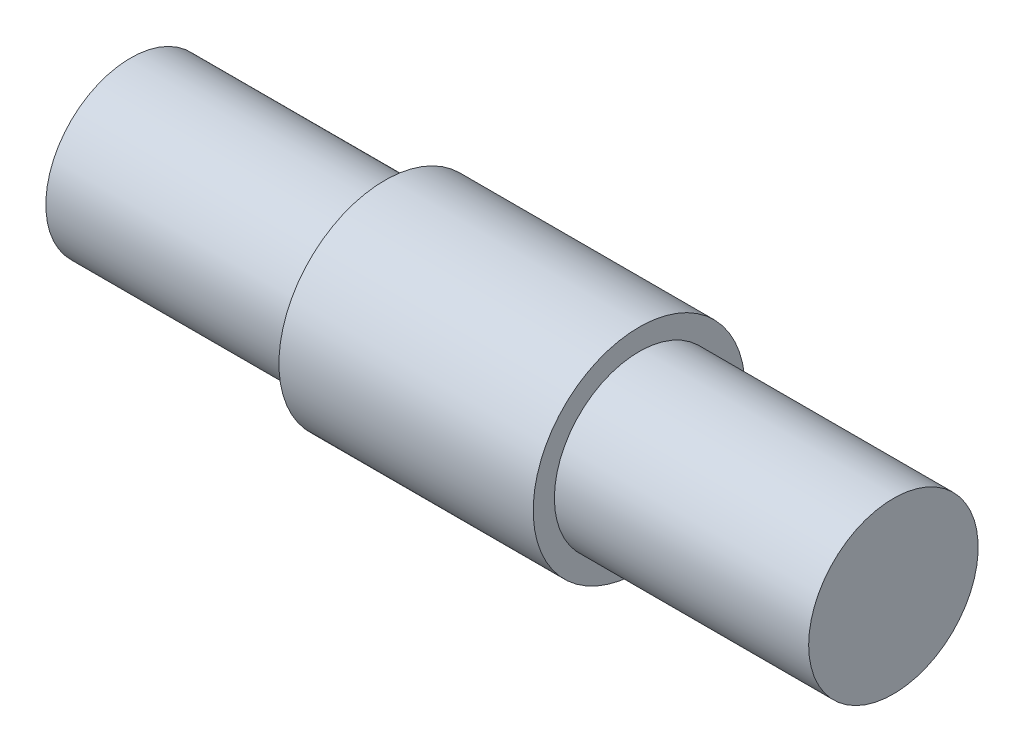
SolidWorks part; units mm, degrees
ref_plane "Front Plane" through (0, 0, 0) normal (0, 0, 1) x (1, 0, 0)
ref_plane "Top Plane" through (0, 0, 0) normal (0, 1, 0) x (1, 0, 0)
ref_plane "Right Plane" through (0, 0, 0) normal (1, 0, 0) x (0, 0, -1)
sketch "Sketch2" plane through (0, 0, 0) normal (1, 0, 0) x (0, 0, -1)
  circle A0 centre (0, 0) radius 3.175
  dimension "D1" = 6.35
extrude "Boss-Extrude1" add sketch "Sketch2" along normal mid plane 9.525
sketch "Sketch3" plane through (-4.7625, 0, 0) normal (-1, 0, 0) x (0, 0, 1)
  circle A0 centre (0, 0) radius 3.9688
  dimension "D1" = 7.9375
extrude "Boss-Extrude2" add sketch "Sketch3" along normal blind 9.525
sketch "Sketch5" plane through (-14.2875, 0, 0) normal (-1, 0, 0) x (0, 0, 1)
  circle A0 centre (0, 0) radius 3.175
  dimension "D1" = 6.35
extrude "Boss-Extrude3" add sketch "Sketch5" along normal blind 9.525
